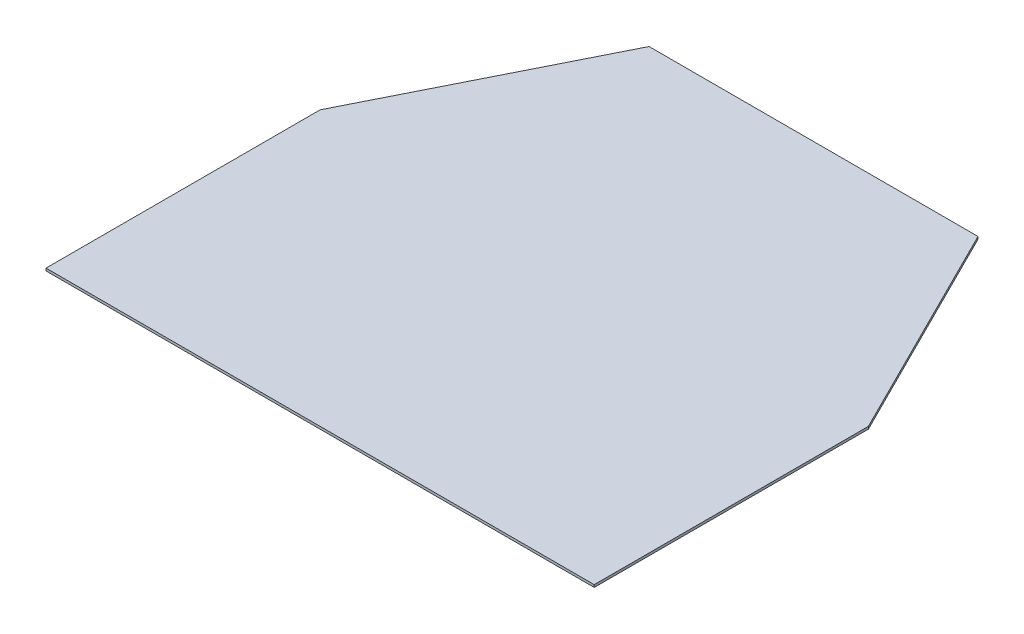
SolidWorks part; units mm, degrees
ref_plane "Front Plane" through (0, 0, 0) normal (0, 0, 1) x (1, 0, 0)
ref_plane "Top Plane" through (0, 0, 0) normal (0, 1, 0) x (1, 0, 0)
ref_plane "Right Plane" through (0, 0, 0) normal (1, 0, 0) x (0, 0, -1)
sketch "Sketch2" plane through (0, 0, 0) normal (0, 1, 0) x (1, 0, 0)
  line L1 (-254, -228.6) -> (254, -228.6)
  line L2 (-254, -228.6) -> (-254, 228.6)
  line L3 (-254, 228.6) -> (254, 228.6)
  line L4 (254, -228.6) -> (254, 228.6)
  line L5 (-254, -228.6) -> (254, 228.6) construction
  line L6 (-254, 228.6) -> (254, -228.6) construction
  point P0 (0, 0)
  dimension "D1" = 508
  dimension "D2" = 457.2
extrude "Boss-Extrude1" add sketch "Sketch2" along normal blind 2.286
chamfer "Chamfer1" distance 203.2 distance2 101.6 1 edges at (254, 1.143, -228.6)
chamfer "Chamfer2" distance 101.6 distance2 203.2 1 edges at (-254, 1.143, -228.6)
